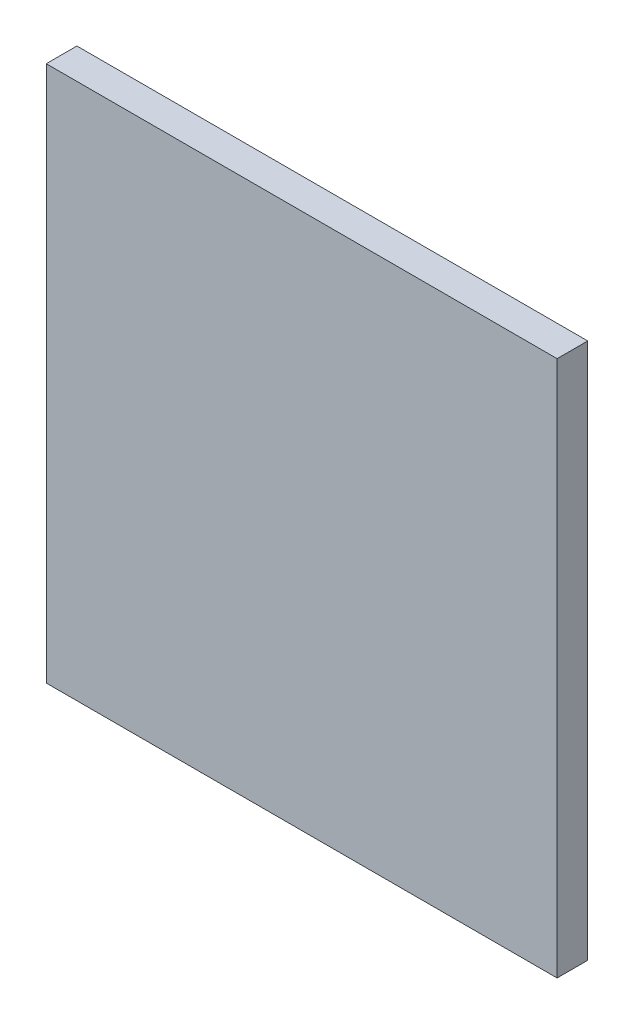
SolidWorks part; units mm, degrees
ref_plane "Front Plane" through (0, 0, 0) normal (0, 0, 1) x (1, 0, 0)
ref_plane "Top Plane" through (0, 0, 0) normal (0, 1, 0) x (1, 0, 0)
ref_plane "Right Plane" through (0, 0, 0) normal (1, 0, 0) x (0, 0, -1)
sketch "Sketch1" plane through (0, 0, 0) normal (0, 0, 1) x (1, 0, 0)
  line L1 (-15, -15.75) -> (15, -15.75)
  line L2 (-15, -15.75) -> (-15, 15.75)
  line L3 (-15, 15.75) -> (15, 15.75)
  line L4 (15, -15.75) -> (15, 15.75)
  line L5 (-15, -15.75) -> (15, 15.75) construction
  line L6 (-15, 15.75) -> (15, -15.75) construction
  point P0 (0, 0)
  dimension "D1" = 30
  dimension "D2" = 31.5
extrude "Boss-Extrude1" add sketch "Sketch1" along normal blind 1.8
